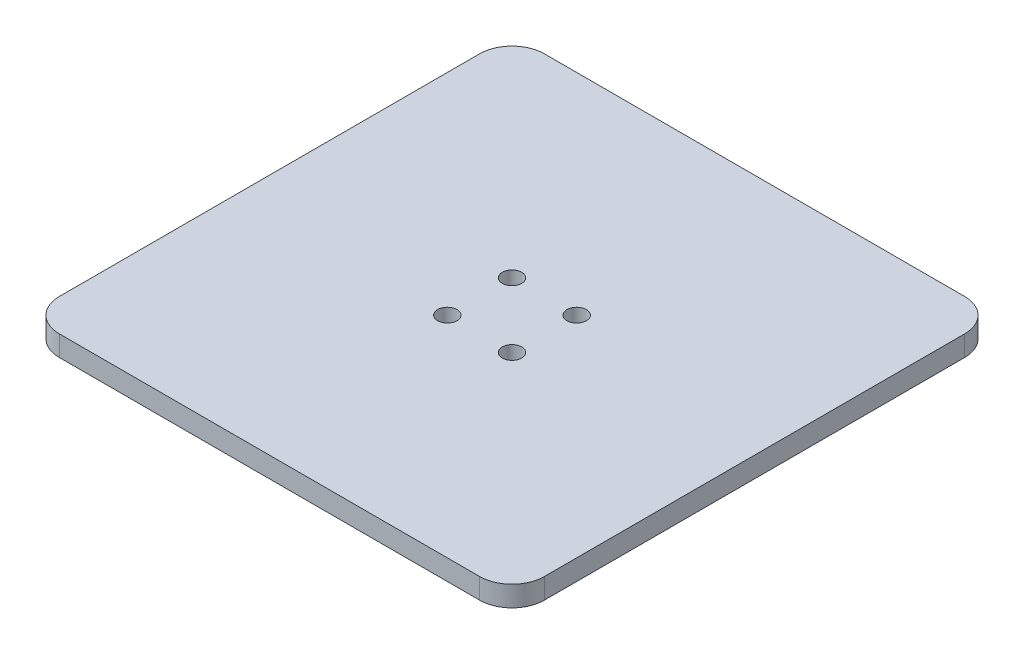
SolidWorks part; units mm, degrees
material "Manganese Bronze"
ref_plane "Front Plane" through (0, 0, 0) normal (0, 0, 1) x (1, 0, 0)
ref_plane "Top Plane" through (0, 0, 0) normal (0, 1, 0) x (1, 0, 0)
ref_plane "Right Plane" through (0, 0, 0) normal (1, 0, 0) x (0, 0, -1)
sketch "Sketch2" plane through (0, 0, 0) normal (0, 1, 0) x (1, 0, 0)
  line L1 (0, 0) -> (-150, 0)
  line L2 (0, 0) -> (0, 150)
  line L3 (0, 150) -> (-150, 150)
  line L4 (-150, 0) -> (-150, 150)
  circle A0 centre (-85, 85) radius 1.25
  circle A1 centre (-65, 85) radius 1.25
  circle A2 centre (-85, 65) radius 1.25
  circle A3 centre (-65, 65) radius 1.25
  dimension "D3" = 2.5
  dimension "D4" = 2.5
  dimension "D5" = 2.5
  dimension "D6" = 2.5
  dimension "D1" = 150
  dimension "D2" = 150
  dimension "D7" = 20
  dimension "D8" = 20
  dimension "D9" = 20
  dimension "D10" = 0
  dimension "D11" = 0
  dimension "D12" = 0
  dimension "D13" = 65
  dimension "D14" = 65
extrude "Boss-Extrude1" add sketch "Sketch2" along normal blind 6.35
fillet "Fillet1" radius 10 4 edges at (0, 3.175, -150) (-150, 3.175, -150) (-150, 3.175, 0) (0, 3.175, 0)
sketch "Sketch3" plane through (0, 6.35, 0) normal (0, 1, 0) x (1, 0, 0)
  circle A0 centre (-85, 85) radius 3
  circle A1 centre (-65, 85) radius 3
  circle A2 centre (-85, 65) radius 3
  circle A3 centre (-65, 65) radius 3
  dimension "D1" = 6
  dimension "D2" = 6
  dimension "D3" = 6
  dimension "D4" = 6
extrude "Cut-Extrude1" cut sketch "Sketch3" against normal blind 4.3
sketch "Sketch4" plane through (0, 0, 0) normal (0, -1, 0) x (1, 0, 0)
  line L0 (0, -10) -> (0, -140) construction
  line L5 (-91.1, -60) -> (-58.9, -60)
  line L6 (-91.1, -60) -> (-91.1, -90)
  line L7 (-91.1, -90) -> (-58.9, -90)
  line L8 (-58.9, -60) -> (-58.9, -90)
  line L12 (-10, -150) -> (-140, -150) construction
  circle A2 centre (-85, -65) radius 1.25
  circle A3 centre (-85, -85) radius 1.25
  circle A4 centre (-65, -85) radius 1.25
  circle A5 centre (-65, -65) radius 1.25
  dimension "D1" = 32.2
  dimension "D2" = 30
  dimension "D3" = 58.9
  dimension "D4" = 60
extrude "Boss-Extrude2" add sketch "Sketch4" along normal blind 9
